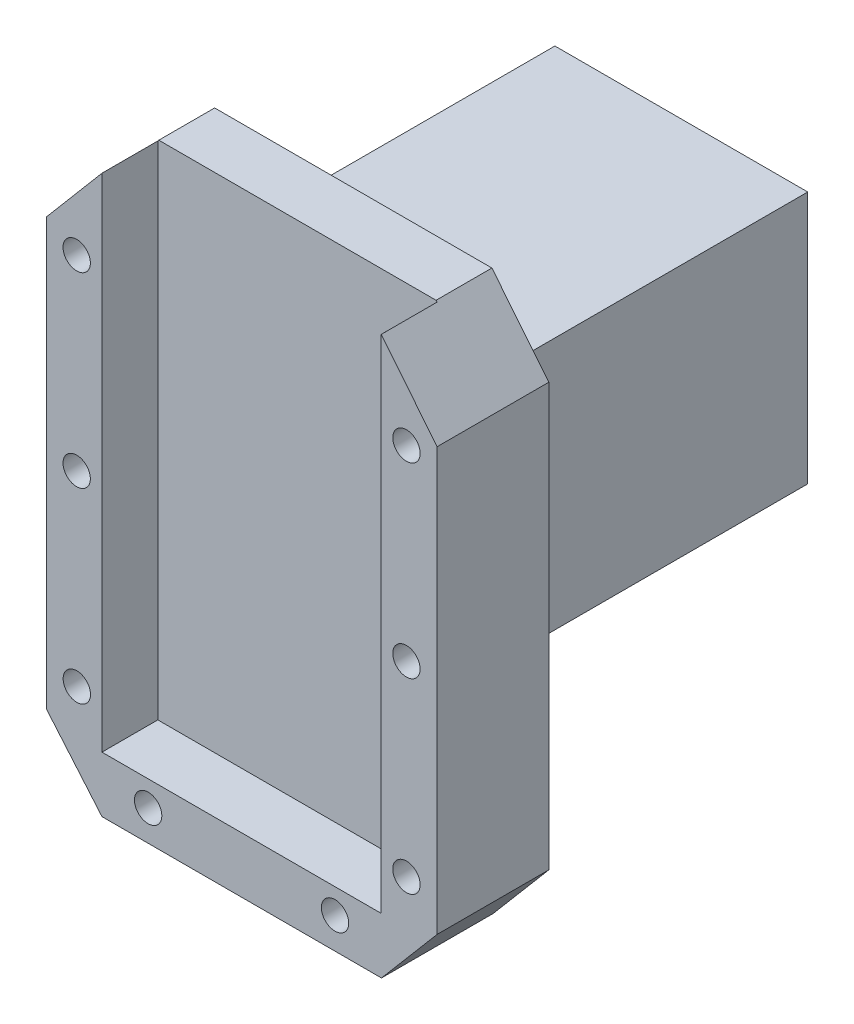
SolidWorks part; units mm, degrees
material "PET"
ref_plane "Front Plane" through (0, 0, 0) normal (0, 0, 1) x (1, 0, 0)
ref_plane "Top Plane" through (0, 0, 0) normal (0, 1, 0) x (1, 0, 0)
ref_plane "Right Plane" through (0, 0, 0) normal (1, 0, 0) x (0, 0, -1)
sketch "Sketch1" plane through (0, 0, 0) normal (0, 0, 1) x (1, 0, 0)
  line L1 (0, 0) -> (-35.56, 0)
  line L2 (0, 0) -> (0, 50.8)
  line L3 (0, 50.8) -> (-35.56, 50.8)
  line L4 (-35.56, 0) -> (-35.56, 50.8)
  dimension "D1" = 50.8
  dimension "D2" = 35.56
extrude "Boss-Extrude1" add sketch "Sketch1" along normal blind 10.16
sketch "Sketch2" plane through (0, 0, 10.16) normal (0, 0, 1) x (1, 0, 0)
  line L0 (0, 50.8) -> (-35.56, 50.8) construction
  line L1 (-30.4926, 50.8) -> (-5.0926, 50.8)
  line L2 (-30.4926, 50.8) -> (-30.4926, 5.08)
  line L3 (-30.4926, 5.08) -> (-5.0926, 5.08)
  line L4 (-5.0926, 50.8) -> (-5.0926, 5.08)
  dimension "D1" = 45.72
  dimension "D2" = 25.4
extrude "Cut-Extrude2" cut sketch "Sketch2" against normal blind 5.08
hole_wizard "#40 (0.098) Diameter Hole1" positions "Sketch6" profile "Sketch5" hole size "#40" standard "ANSI Inch" end condition through all
sketch "Sketch6" plane through (0, 0, 0) normal (0, 0, -1) x (-1, 0, 0)
  point P0 (2.7924, 43.0871)
  point P2 (2.7924, 26.093)
  point P4 (2.7924, 9.1052)
  point P6 (9.2907, 2.8227)
  point P8 (26.2924, 2.7871)
  point P10 (32.78, 9.1052)
  point P12 (32.7924, 26.0871)
  point P14 (32.7924, 43.0871)
sketch "Sketch5" plane through (-2.7924, 43.0871, 0) normal (1, 0, 0) x (0, 1, 0)
  line L0 (0, 0) -> (0, 10.16)
  line L1 (0, 10.16) -> (1.2446, 10.16)
  line L2 (1.2446, 10.16) -> (1.2446, 0)
  line L5 (1.2446, 0) -> (0, 0)
  line L11 (0, -6.35) -> (0, 107.95) construction
  dimension "Thru Hole Dia." = 2.4892
  dimension "Thru Hole Depth" = 10.16
sketch "Sketch7" plane through (0, 0, 0) normal (0, 0, -1) x (-1, 0, 0)
  line L0 (15.0265, 33.6834) -> (21.0265, 33.6834)
  line L1 (21.0265, 33.6834) -> (24.0265, 36.6834)
  line L2 (24.0265, 36.6834) -> (24.0265, 37.6834)
  line L3 (24.0265, 37.6834) -> (21.0265, 37.6834)
  line L4 (21.0265, 37.6834) -> (21.0265, 39.7573)
  line L5 (21.0265, 39.7573) -> (28.1077, 39.7573)
  line L6 (28.1077, 39.7573) -> (28.1077, 32.5954)
  line L7 (28.1077, 32.5954) -> (26.0219, 32.5954)
  line L8 (26.0219, 32.5954) -> (26.0265, 35.6834)
  line L9 (26.0265, 35.6834) -> (25.0265, 35.6834)
  line L10 (25.0265, 35.6834) -> (22.0265, 32.6834)
  line L11 (22.0265, 32.6834) -> (22.0265, 26.6834)
  line L12 (6.4475, 41.1565) -> (29.4475, 41.1565)
  line L13 (6.4475, 41.1565) -> (6.4475, 18.1565)
  line L14 (6.4475, 18.1565) -> (29.4475, 18.1565)
  line L15 (29.4475, 41.1565) -> (29.4475, 18.1565)
  line L16 (22.0265, 26.6834) -> (25.0265, 23.6834)
  line L17 (25.0265, 23.6834) -> (26.0265, 23.6834)
  line L18 (26.0265, 23.6834) -> (26.0265, 26.6834)
  line L19 (26.0265, 26.6834) -> (28.0265, 26.6834)
  line L20 (28.0265, 26.6834) -> (28.0265, 19.6311)
  line L21 (28.0265, 19.6311) -> (21.0265, 19.6834)
  line L22 (21.0265, 19.6834) -> (21.0265, 21.6834)
  line L23 (21.0265, 21.6834) -> (24.0265, 21.6834)
  line L24 (24.0265, 21.6834) -> (24.0265, 22.6834)
  line L25 (24.0265, 22.6834) -> (21.0265, 25.6834)
  line L26 (21.0265, 25.6834) -> (15.0265, 25.6834)
  line L27 (15.0265, 25.6834) -> (12.0265, 22.6834)
  line L28 (12.0265, 22.6834) -> (12.0265, 21.6834)
  line L29 (12.0265, 21.6834) -> (15.0265, 21.6834)
  line L30 (15.0265, 21.6834) -> (15.0265, 19.6834)
  line L31 (15.0265, 19.6834) -> (7.9714, 19.6834)
  line L32 (7.9714, 19.6834) -> (8.0265, 26.6834)
  line L33 (8.0265, 26.6834) -> (10.0265, 26.6834)
  line L34 (10.0265, 26.6834) -> (10.0265, 23.6834)
  line L35 (10.0265, 23.6834) -> (11.0265, 23.6834)
  line L36 (11.0265, 23.6834) -> (14.0265, 26.6834)
  line L37 (14.0265, 26.6834) -> (14.0265, 32.6834)
  line L38 (14.0265, 32.6834) -> (11.0265, 35.6834)
  line L39 (11.0265, 35.6834) -> (10.0265, 35.6834)
  line L40 (10.0265, 35.6834) -> (10.0265, 32.6834)
  line L41 (10.0265, 32.6834) -> (8.0265, 32.6834)
  line L42 (8.0265, 32.6834) -> (8.0265, 39.7573)
  line L43 (8.0265, 39.7573) -> (15.0979, 39.7573)
  line L44 (15.0979, 39.7573) -> (15.0265, 37.6834)
  line L45 (15.0265, 37.6834) -> (12.0265, 37.6834)
  line L46 (12.0265, 37.6834) -> (12.0265, 36.6834)
  line L47 (12.0265, 36.6834) -> (15.0265, 33.6834)
extrude "Boss-Extrude2" add sketch "Sketch7" along normal blind 30
fillet "Fillet1" radius 1.778 4 edges at (-29.4475, 29.6565, 0) (-17.9475, 18.1565, 0) (-6.4475, 29.6565, 0) (-17.9475, 41.1565, 0)
sketch "Sketch8" plane through (0, 0, 10.16) normal (0, 0, 1) x (1, 0, 0)
  line L0 (-5.179, 50.8) -> (0, 44.3921)
  line L1 (-5.0926, 50.8) -> (-30.4926, 50.8) construction
  line L2 (0, 0) -> (0, 50.8) construction
  line L3 (-0.1773, 44.6007) -> (-5.2773, 50.6007) construction
  line L4 (0, 44.3921) -> (0, 50.8)
  line L5 (0, 50.8) -> (-5.179, 50.8)
  line L6 (-35.56, 44.7066) -> (-35.56, 50.8)
  line L7 (-35.56, 50.8) -> (-35.56, 0) construction
  line L8 (-35.56, 50.8) -> (-30.4026, 50.8)
  line L9 (-30.4026, 50.8) -> (-35.56, 44.7066)
  line L10 (-35.56, 5.97) -> (-35.56, 0)
  line L11 (-35.56, 0) -> (-30.4926, 0)
  line L12 (-35.56, 0) -> (0, 0) construction
  line L13 (-30.4926, 0) -> (-35.56, 5.97)
  line L14 (-5.0926, -0.0313) -> (0, 0)
  line L15 (0, 0) -> (0, 5.97)
  line L16 (0, 5.97) -> (-5.0926, -0.0313)
extrude "Cut-Extrude3" cut sketch "Sketch8" against normal through all
